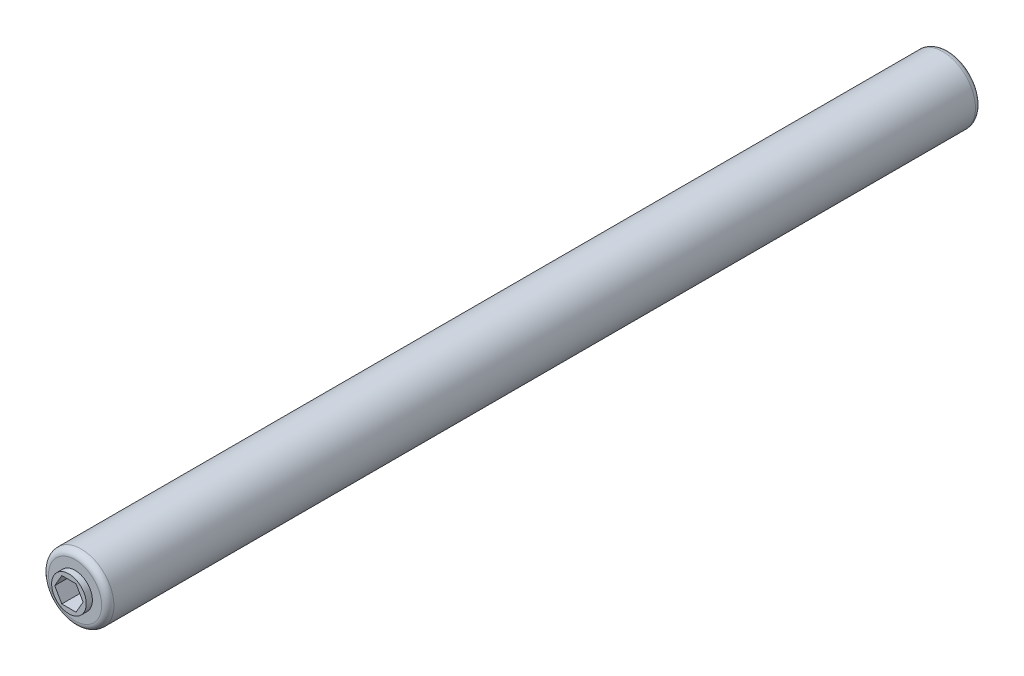
SolidWorks part; units mm, degrees
ref_plane "Front Plane" through (0, 0, 0) normal (0, 0, 1) x (1, 0, 0)
ref_plane "Top Plane" through (0, 0, 0) normal (0, 1, 0) x (1, 0, 0)
ref_plane "Right Plane" through (0, 0, 0) normal (1, 0, 0) x (0, 0, -1)
sketch "Sketch1" plane through (0, 0, 0) normal (0, 0, 1) x (1, 0, 0)
  circle A0 centre (0, 0) radius 16.8672
  dimension "D1" = 33.7344
extrude "Boss-Extrude1" add sketch "Sketch1" along normal mid plane 457.2
sketch "Sketch2" plane through (0, 0, 0) normal (0, 1, 0) x (1, 0, 0)
  line L0 (0, 0) -> (50000, 0) construction
  line L2 (16.8672, -228.6) -> (8.9297, -228.6)
  line L3 (16.8672, -228.6) -> (16.8672, -225.425)
  line L4 (16.8672, -225.425) -> (8.9297, -225.425)
  line L5 (8.9297, -228.6) -> (8.9297, -225.425)
  line L15 (8.9297, 228.6) -> (8.9297, 225.425)
  line L16 (16.8672, 225.425) -> (8.9297, 225.425)
  line L17 (16.8672, 228.6) -> (16.8672, 225.425)
  line L18 (16.8672, 228.6) -> (8.9297, 228.6)
  line L19 (0, 0) -> (0, 50000) construction
  dimension "D1" = 3.175
  dimension "D2" = 7.9375
revolve "Cut-Revolve1" cut sketch "Sketch2" angle 360 about L19
fillet "Fillet1" radius 3.175 2 edges at (16.8672, 0, 225.425) (16.8672, 0, -225.425)
sketch "Sketch3" plane through (0, 0, 228.6) normal (0, 0, 1) x (1, 0, 0)
  line L1 (7.3323, 0) -> (3.6662, 6.35)
  line L2 (3.6662, 6.35) -> (-3.6662, 6.35)
  line L3 (-3.6662, 6.35) -> (-7.3323, 0)
  line L4 (-7.3323, 0) -> (-3.6662, -6.35)
  line L5 (-3.6662, -6.35) -> (3.6662, -6.35)
  line L6 (3.6662, -6.35) -> (7.3323, 0)
  circle A0 centre (0, 0) radius 6.35 construction
  dimension "D1" = 12.7
extrude "Cut-Extrude1" cut sketch "Sketch3" against normal through all
